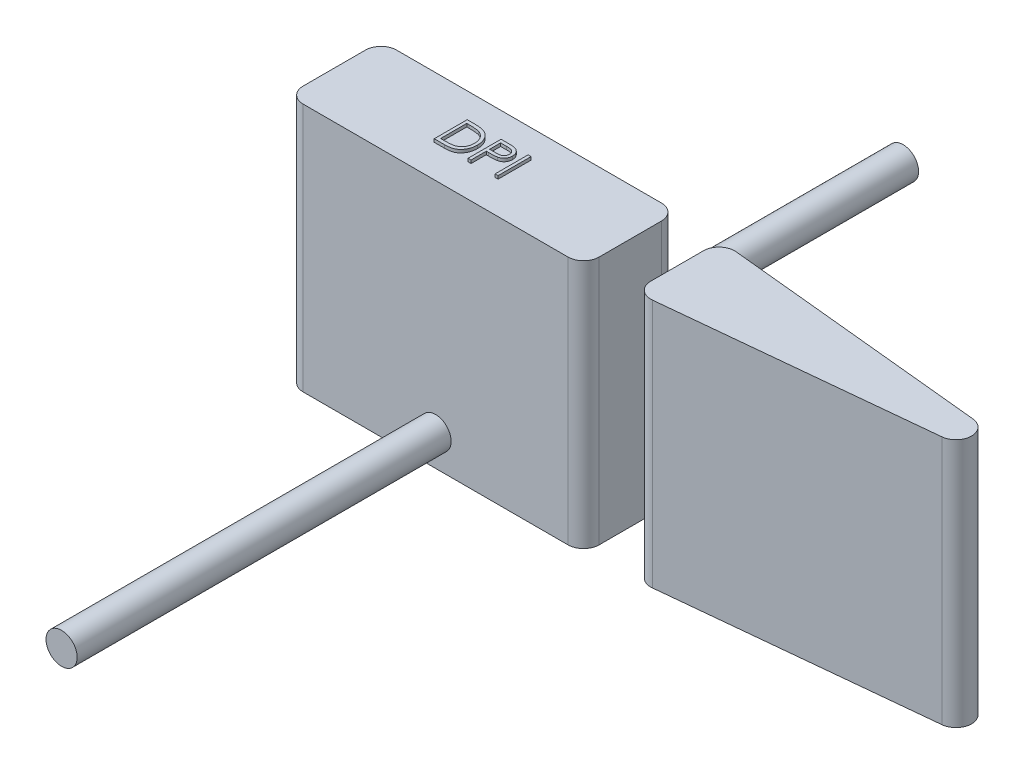
SolidWorks part; units mm, degrees
material "Silicon Rubber"
ref_plane "Front Plane" through (0, 0, 0) normal (0, 0, 1) x (1, 0, 0)
ref_plane "Top Plane" through (0, 0, 0) normal (0, 1, 0) x (1, 0, 0)
ref_plane "Right Plane" through (0, 0, 0) normal (1, 0, 0) x (0, 0, -1)
sketch "Sketch1" plane through (0, 0, 0) normal (0, 1, 0) x (1, 0, 0)
  line L0 (-8.2814, 0) -> (25.25, 0) construction
  line L1 (-5.25, 2) -> (5.25, 2)
  line L2 (-5.25, 2) -> (-5.25, -2)
  line L3 (-5.25, -2) -> (5.25, -2)
  line L4 (5.25, 2) -> (5.25, -2)
  line L5 (-5.25, 2) -> (5.25, -2) construction
  line L6 (-5.25, -2) -> (5.25, 2) construction
  line L7 (5.75, 1.95) -> (25.25, 0)
  line L8 (25.25, 0) -> (5.75, -1.95)
  line L9 (5.75, 1.95) -> (5.75, -1.95)
  line L10 (-4.75, 1.5) -> (4.75, 1.5)
  line L11 (4.75, 1.5) -> (4.75, -1.5)
  line L12 (-4.75, -1.5) -> (4.75, -1.5)
  line L13 (-4.75, 1.5) -> (-4.75, -1.5)
  line L14 (6.25, 1.3975) -> (20.2251, 0)
  line L15 (20.2251, 0) -> (6.25, -1.3975)
  line L16 (6.25, 1.3975) -> (6.25, -1.3975)
  point P0 (0, 0)
  dimension "D1" = 4
  dimension "D2" = 10.5
  dimension "D3" = 19.5
  dimension "D4" = 0.5
  dimension "D5" = 5.711
  dimension "D6" = 0.5
  dimension "D7" = 0.5
extrude "Boss-Extrude1" add sketch "Sketch1" along normal blind 8 contours L10 L11 L12 L13 | L14 L15 L16
fillet "Fillet1" radius 0.5 4 edges at (4.75, 4, -1.5) (4.75, 4, 1.5) (-4.75, 4, -1.5) (-4.75, 4, 1.5)
fillet "Fillet2" radius 0.5 3 edges at (20.2251, 4, 0) (6.25, 4, 1.3975) (6.25, 4, -1.3975)
sketch "Sketch3" plane through (0, 0, 0) normal (0, 1, 0) x (1, 0, 0)
  text T0 "DPI" font "Century Gothic" height in points 4
extrude "Boss-Extrude2" add sketch "Sketch3" along normal offset from surface (8.1 mm away) 0.1 up to face at (0, 8, 0) offset beyond the face yes
sketch "Sketch4" plane through (0, 0, 1.5) normal (0, 0, 1) x (1, 0, 0)
  line L0 (0, 0) -> (0, 2) construction
  circle A0 centre (0, 1) radius 0.5
  point P5 (0, 0)
  dimension "D1" = 1
  dimension "D2" = 1
extrude "Boss-Extrude3" add sketch "Sketch4" along normal blind 12
sketch "Sketch5" plane through (0, 0, -1.5) normal (0, 0, -1) x (-1, 0, 0)
  line L0 (0, 0) -> (0, 2.1627) construction
  circle A0 centre (0, 1) radius 0.5
  dimension "D1" = 1
  dimension "D2" = 1
extrude "Boss-Extrude4" add sketch "Sketch5" along normal blind 12
